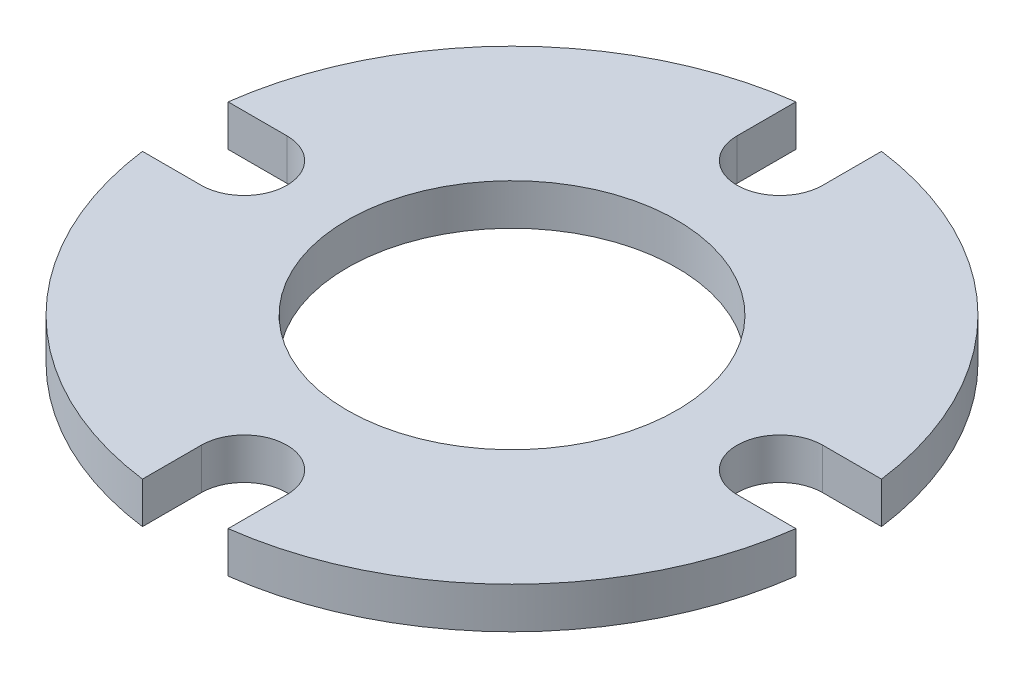
SolidWorks part; units mm, degrees
ref_plane "Front Plane" through (0, 0, 0) normal (0, 0, 1) x (1, 0, 0)
ref_plane "Top Plane" through (0, 0, 0) normal (0, 1, 0) x (1, 0, 0)
ref_plane "Right Plane" through (0, 0, 0) normal (1, 0, 0) x (0, 0, -1)
sketch "Sketch1" plane through (0, 0, 0) normal (0, 1, 0) x (1, 0, 0)
  line L0 (0, 1) -> (0, -1) construction
  line L1 (1, 0) -> (-1, 0) construction
  line L2 (0.813, 0.2714) -> (0.813, -0.1956) construction
  line L3 (0.813, -0.13) -> (0.9915, -0.13)
  line L4 (0.813, 0.13) -> (0.9915, 0.13)
  line L5 (-0.13, -0.813) -> (-0.13, -0.9915)
  line L6 (0.13, -0.813) -> (0.13, -0.9915)
  line L7 (-0.813, 0.13) -> (-0.9915, 0.13)
  line L8 (-0.813, -0.13) -> (-0.9915, -0.13)
  line L9 (0.13, 0.813) -> (0.13, 0.9915)
  line L10 (-0.13, 0.813) -> (-0.13, 0.9915)
  arc A0 (0.9915, 0.13) -> (0.13, 0.9915) centre (0, 0) ccw
  circle A1 centre (0, 0) radius 0.5
  arc A2 (0.813, 0.13) -> (0.813, -0.13) centre (0.813, 0) ccw
  arc A3 (0.13, -0.813) -> (-0.13, -0.813) centre (0, -0.813) ccw
  arc A4 (-0.813, -0.13) -> (-0.813, 0.13) centre (-0.813, 0) ccw
  arc A5 (-0.13, 0.813) -> (0.13, 0.813) centre (0, 0.813) ccw
  arc A6 (-0.13, 0.9915) -> (-0.9915, 0.13) centre (0, 0) ccw
  arc A7 (-0.9915, -0.13) -> (-0.13, -0.9915) centre (0, 0) ccw
  arc A8 (0.13, -0.9915) -> (0.9915, -0.13) centre (0, 0) ccw
  point P1 (0, 0)
  point P11 (0.813, 0.2714)
  point P16 (0, 0)
  point P32 (0, 0)
  point P33 (0, 0)
  point P34 (0, 0)
  point P35 (0, 0)
  dimension "D1" = 1
  dimension "D2" = 2
  dimension "D4" = 0.26
  dimension "D7" = 0.13
  dimension "D3" = 0.813
  dimension "D6" = 0.813
  dimension "D5" = 4
extrude "Boss-Extrude1" add sketch "Sketch1" along normal mid plane 0.125 contours A6 L7 A4 L8 A7 L5 A3 L6 A8 L3 A2 L4 A0 L9 A5 L10 | A1
